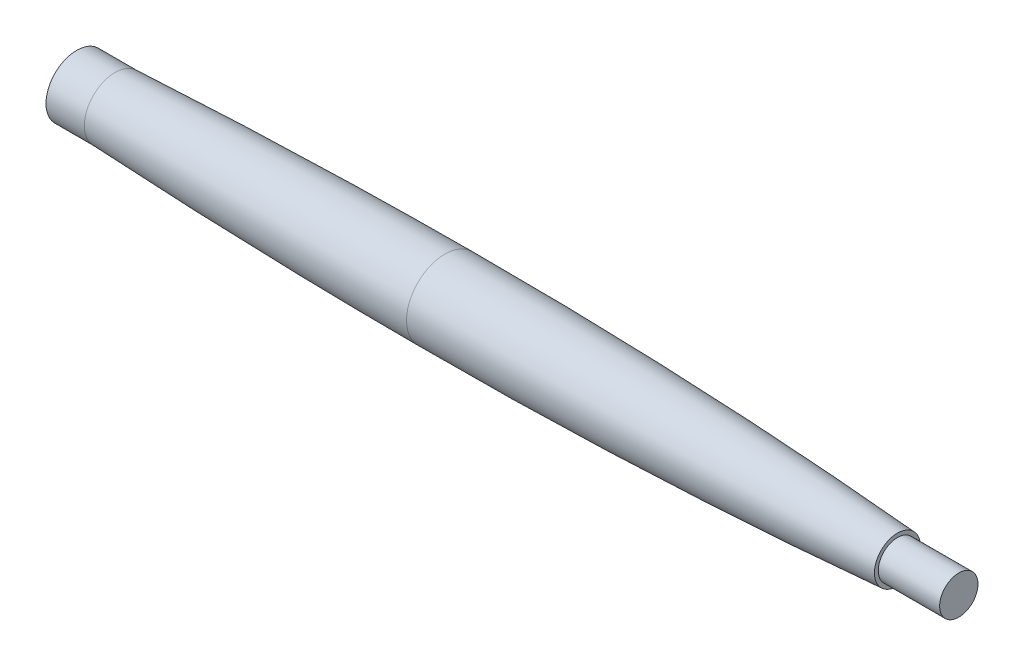
SolidWorks part; units mm, degrees
ref_plane "Front Plane" through (0, 0, 0) normal (0, 0, 1) x (1, 0, 0)
ref_plane "Top Plane" through (0, 0, 0) normal (0, 1, 0) x (1, 0, 0)
ref_plane "Right Plane" through (0, 0, 0) normal (1, 0, 0) x (0, 0, -1)
sketch "Sketch1" plane through (0, 0, 0) normal (0, 0, 1) x (1, 0, 0)
  line L0 (-43, 0) -> (0, 0) construction
  line L1 (0, 0) -> (59, 0) construction
  line L2 (-43, 4) -> (-43, 0)
  line L3 (-43, 0) -> (0, 0)
  line L4 (0, 0) -> (59, 0)
  line L5 (59, 0) -> (59, 3)
  arc A0 (-43, 4) -> (0, 5) centre (2.2062, -1014.8682) cw
  arc A1 (0, 5) -> (59, 3) centre (1.7717, -813.9856) cw
  point P9 (0, 0)
  dimension "D3" = 5
  dimension "D1" = 43
  dimension "D2" = 59
  dimension "D4" = 3
  dimension "D5" = 4
revolve "Revolve1" add sketch "Sketch1" angle 360 about L4
sketch "Sketch2" plane through (-43, 0, 0) normal (-1, 0, 0) x (0, 0, 1)
  circle A0 centre (0, 0) radius 4 construction
  circle A1 centre (0, 0) radius 4
extrude "Boss-Extrude1" add sketch "Sketch2" along normal blind 5 separate body
sketch "Sketch3" plane through (59, 0, 0) normal (1, 0, 0) x (0, 0, -1)
  circle A0 centre (0, 0) radius 2.5
  dimension "D1" = 5
extrude "Boss-Extrude2" add sketch "Sketch3" along normal blind 8
